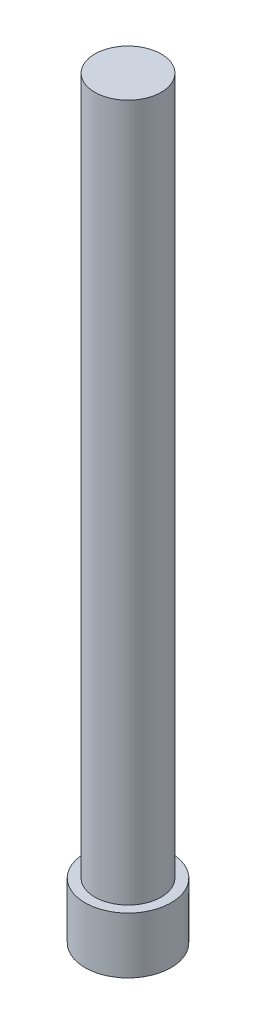
SolidWorks part; units mm, degrees
ref_plane "Front Plane" through (0, 0, 0) normal (0, 0, 1) x (1, 0, 0)
ref_plane "Top Plane" through (0, 0, 0) normal (0, 1, 0) x (1, 0, 0)
ref_plane "Right Plane" through (0, 0, 0) normal (1, 0, 0) x (0, 0, -1)
sketch "Sketch1" plane through (0, 0, 0) normal (0, 1, 0) x (1, 0, 0)
  circle A0 centre (0, 0) radius 0.75
  dimension "D1" = 1.5
extrude "Boss-Extrude1" add sketch "Sketch1" along normal blind 15.748
sketch "Sketch2" plane through (0, 15.748, 0) normal (0, 1, 0) x (1, 0, 0)
  circle A0 centre (0, 0) radius 0.9715
sketch "Sketch3" plane through (0, 0, 0) normal (0, -1, 0) x (1, 0, 0)
  circle A0 centre (0, 0) radius 0.9715
extrude "Boss-Extrude3" add sketch "Sketch3" along normal blind 1.27
